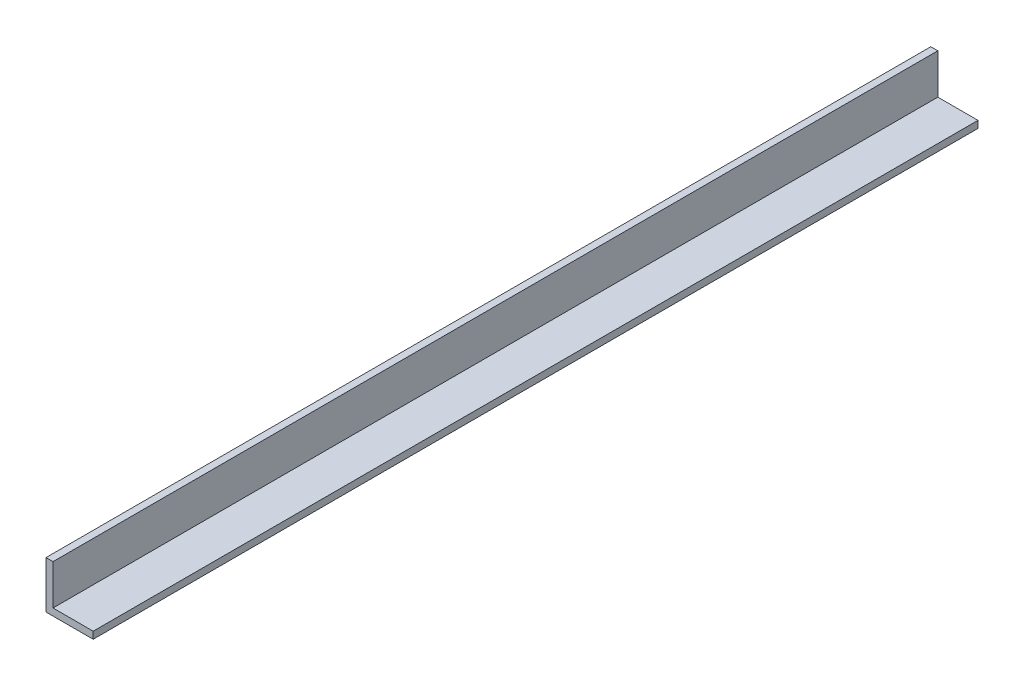
SolidWorks part; units mm, degrees
ref_plane "Alzado" through (0, 0, 0) normal (0, 0, 1) x (1, 0, 0)
ref_plane "Planta" through (0, 0, 0) normal (0, 1, 0) x (1, 0, 0)
ref_plane "Vista lateral" through (0, 0, 0) normal (1, 0, 0) x (0, 0, -1)
sketch "Croquis1" plane through (0, 0, 0) normal (0, 0, 1) x (1, 0, 0)
  line L0 (0, 0) -> (0, 27.24)
  line L1 (0, 27.24) -> (-4.7625, 27.24)
  line L2 (-4.7625, 27.24) -> (-4.7625, -4.76)
  line L3 (-4.7625, -4.76) -> (27.2375, -4.76)
  line L4 (27.2375, -4.76) -> (27.2375, 0)
  line L5 (27.2375, 0) -> (0, 0)
  dimension "D1" = 4.7625
  dimension "D2" = 32
  dimension "D3" = 32
  dimension "D4" = 4.76
extrude "Saliente-Extruir1" add sketch "Croquis1" along normal mid plane 600
